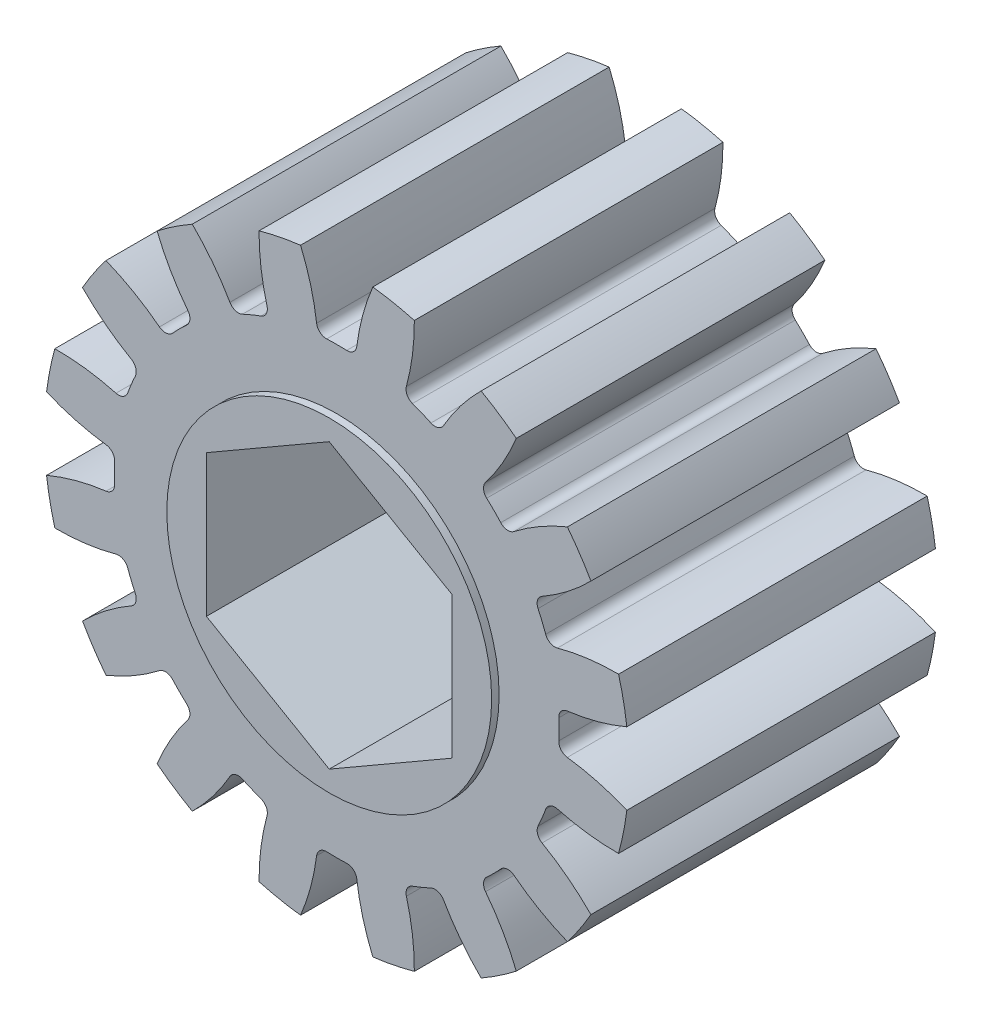
SolidWorks part; units mm, degrees
material "7075-T6 (SN)"
ref_plane "Alzado" through (0, 0, 0) normal (0, 0, 1) x (1, 0, 0)
ref_plane "Planta" through (0, 0, 0) normal (0, 1, 0) x (1, 0, 0)
ref_plane "Vista lateral" through (0, 0, 0) normal (1, 0, 0) x (0, 0, -1)
sketch "Croquis1" plane through (0, 0, 0) normal (0, 0, 1) x (1, 0, 0)
  circle A0 centre (0, 0) radius 10.16 construction
  circle A1 centre (0, 0) radius 11.43
  dimension "D" = 20.32
  dimension "OD" = 22.86
extrude "Saliente-Extruir1" add sketch "Croquis1" along normal mid plane 12.065
sketch "Croquis2" plane through (0, 0, 0) normal (0, 0, 1) x (1, 0, 0)
  line L0 (0, 0) -> (0, 11.43) construction
  line L1 (0, 0) -> (4.3741, 10.5599) construction
  line L2 (0, 0) -> (2.2299, 11.2104) construction
  line L3 (-0.7471, 8.6584) -> (0, 0) construction
  line L4 (-0.9959, 10.1111) -> (0.9959, 10.1111) construction
  line L5 (0.9959, 10.1111) -> (2.9493, 9.7225) construction
  line L6 (-1.3173, 11.3538) -> (0, 6.2604) construction
  circle A0 centre (0, 0) radius 11.43 construction
  arc A2 (0.7471, 8.6584) -> (-0.7471, 8.6584) centre (0, 0) ccw
  circle A5 centre (0, 0) radius 10.16 construction
  arc A6 (-1.4131, 11.3423) -> (-0.7471, 8.6584) centre (-9.5499, 7.8988) cw
  arc A7 (1.4131, 11.3423) -> (0.7471, 8.6584) centre (9.5499, 7.8988) ccw
  arc A8 (1.4131, 11.3423) -> (-1.4131, 11.3423) centre (0, 0) ccw
  dimension "D1" = 22.5
  dimension "D2" = 11.25
  dimension "B" = 1.4694
  dimension "Pressure Angle" = 14.5
extrude "Cortar-Extruir1" cut sketch "Croquis2" against normal through all both and the other way through all
fillet "Redondeo1" radius 0.381 2 edges at (0.7471, 8.6584, 0) (-0.7471, 8.6584, 0)
pattern_circular "MatrizC1" count 16 over 360 about axis through (0, 0, 0) along (0, 0, 1) of "Cortar-Extruir1", "Redondeo1"
sketch "Croquis3" plane through (0, 0, 0) normal (0, 0, 1) x (1, 0, 0)
  circle A0 centre (0, 0) radius 6.35
  dimension "sp" = 12.7
extrude "Saliente-Extruir2" add sketch "Croquis3" along normal mid plane 12.6492
sketch "Croquis4" plane through (0, 0, 0) normal (0, 0, 1) x (1, 0, 0)
  line L1 (0, 5.5433) -> (-4.8006, 2.7716)
  line L2 (-4.8006, 2.7716) -> (-4.8006, -2.7716)
  line L3 (-4.8006, -2.7716) -> (0, -5.5433)
  line L4 (0, -5.5433) -> (4.8006, -2.7716)
  line L5 (4.8006, -2.7716) -> (4.8006, 2.7716)
  line L6 (4.8006, 2.7716) -> (0, 5.5433)
  circle A0 centre (0, 0) radius 4.8006 construction
  dimension "D1" = 9.6012
extrude "Cortar-Extruir2" cut sketch "Croquis4" against normal through all both and the other way through all
equation "\"Number of teeth\" = 16"
equation "\"Diametral Pitch\"= 20"
equation "\"Pressure Angle\"= 14.5"
equation "\"D@Croquis1\"=\"Number of teeth\"/\"Diametral Pitch\""
equation "\"OD@Croquis1\"=(\"Number of teeth\"+2) /\"Diametral Pitch\""
equation "\"D2@Croquis2\"=(360 / \"Number of teeth\")/ 2."
equation "\"D1@Croquis2\"=360 / \"Number of teeth\""
equation "\"B@Croquis2\"=1.157 / \"Diametral Pitch\""
equation "\"Pressure Angle@Croquis2\" = \"Pressure Angle\""
equation "\"D1@Redondeo1\"=(pi / \"Diametral Pitch\") * .0955"
equation "\"D1@MatrizC1\"=\"Number of teeth\""
equation "\"Tt@Saliente-Extruir1\"=if( \"Number of teeth\"=>30,0.375,0.475)"
